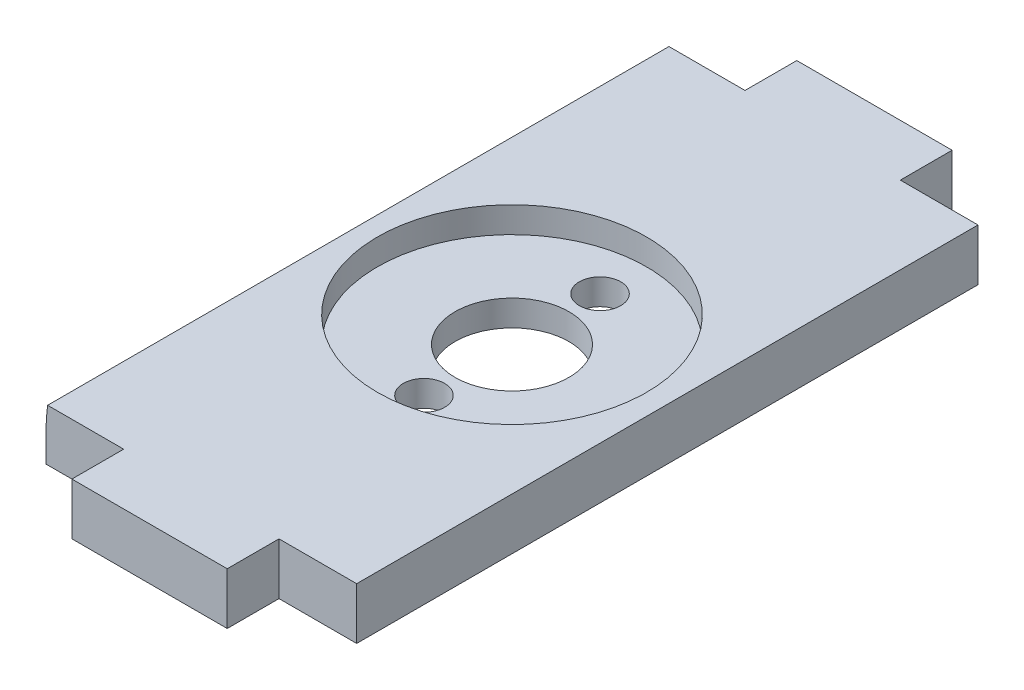
SolidWorks part; units mm, degrees
ref_plane "Front Plane" through (0, 0, 0) normal (0, 0, 1) x (1, 0, 0)
ref_plane "Top Plane" through (0, 0, 0) normal (0, 1, 0) x (1, 0, 0)
ref_plane "Right Plane" through (0, 0, 0) normal (1, 0, 0) x (0, 0, -1)
sketch "Sketch1" plane through (0, 0, 0) normal (0, 1, 0) x (1, 0, 0)
  line L0 (7.5, -30) -> (15, -30)
  line L1 (-15, -30) -> (-7.5, -30)
  line L2 (-15, -30) -> (-15, 30)
  line L3 (-15, 30) -> (-7.5, 30)
  line L4 (15, -30) -> (15, 30)
  line L5 (-15, -30) -> (15, 30) construction
  line L6 (-15, 30) -> (15, -30) construction
  line L8 (-7.5, -30) -> (-7.5, -35)
  line L9 (-7.5, -35) -> (7.5, -35)
  line L10 (7.5, -30) -> (7.5, -35)
  line L12 (-7.5, 30) -> (-7.5, 35)
  line L13 (-7.5, 35) -> (7.5, 35)
  line L14 (7.5, 30) -> (7.5, 35)
  line L15 (7.5, 30) -> (15, 30)
  circle A0 centre (0, 0) radius 5.5
  circle A1 centre (0, 8.5) radius 2
  circle A2 centre (0, -8.5) radius 2
  point P0 (0, 0)
  dimension "D4" = 5
  dimension "D1" = 30
  dimension "D2" = 8.5
  dimension "D3" = 8.5
  dimension "D5" = 15
  dimension "D6" = 7.5
  dimension "D7" = 5
  dimension "D8" = 60
extrude "Boss-Extrude1" add sketch "Sketch1" along normal blind 5
sketch "Sketch2" plane through (0, 5, 0) normal (0, 1, 0) x (1, 0, 0)
  circle A0 centre (0, 0) radius 13
extrude "Cut-Extrude1" cut sketch "Sketch2" against normal blind 2.5
sketch "Sketch3" plane through (0, 0, 30) normal (0, 0, 1) x (1, 0, 0)
  line L0 (-15, 5) -> (-7.5, 5) construction
  line L1 (-15, 5) -> (-15, 0) construction
  line L2 (-15, 5) -> (-15, 2.5)
  line L3 (-15, 5) -> (-14.8431, 5)
  arc A0 (-14.8431, 5) -> (-15, 2.5) centre (5, 2.5) ccw
  dimension "D1" = 2.5
  dimension "D2" = 20
extrude "Cut-Extrude2" cut sketch "Sketch3" against normal up to surface (60 mm away) up to face at (-11.25, 2.5, -30)
